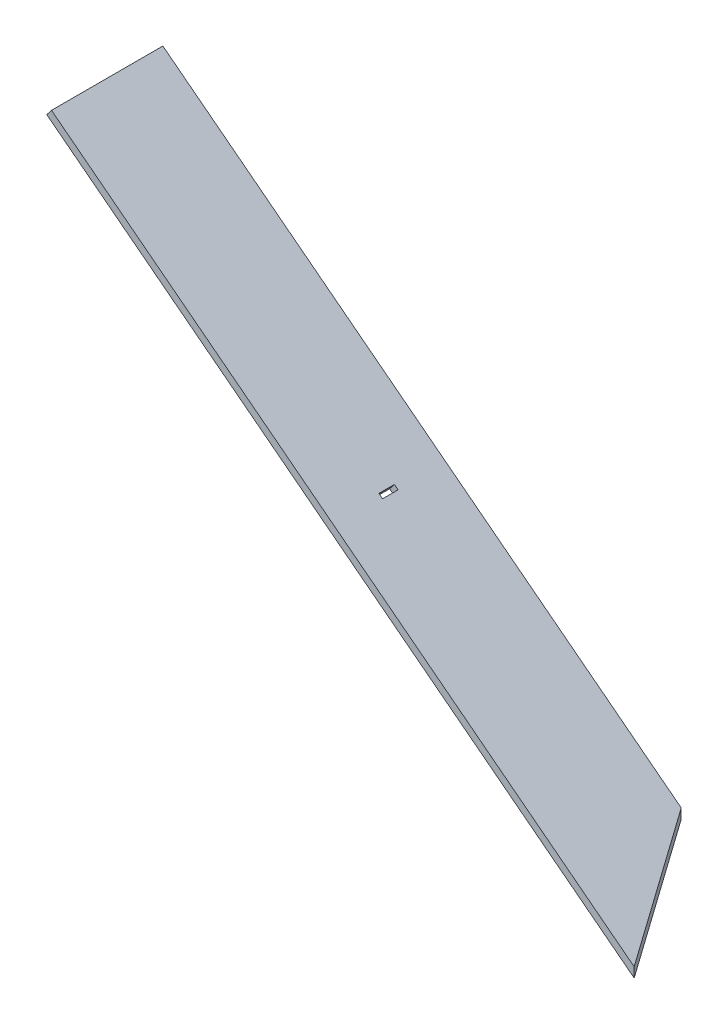
SolidWorks part; units mm, degrees
material "white foam"
ref_plane "Front Plane" through (0, 0, 0) normal (0, 0, 1) x (1, 0, 0)
ref_plane "Top Plane" through (0, 0, 0) normal (0, 1, 0) x (1, 0, 0)
ref_plane "Right Plane" through (0, 0, 0) normal (1, 0, 0) x (0, 0, -1)
sketch "Sketch1" plane through (0, 0, 0) normal (0, 0, 1) x (1, 0, 0)
  line L0 (0, 0) -> (380.0247, 293.7164)
  line L1 (0, 0) -> (-380.0247, 293.7164)
  line L2 (-380.0247, 0) -> (380.0247, 0) construction
  line L3 (0, 6.3193) -> (376.967, 297.6726)
  line L4 (0, 6.3193) -> (-376.967, 297.6726)
  line L5 (380.0247, 293.7164) -> (376.967, 297.6726)
  line L6 (-380.0247, 293.7164) -> (-376.967, 297.6726)
  point P7 (0, 0)
  dimension "D1" = 37.7
  dimension "D2" = 37.7
  dimension "D3" = 480.3
  dimension "D4" = 5
extrude "Boss-Extrude1" add sketch "Sketch1" against normal blind 240.2
sketch "Sketch2" plane through (0, 0, 0) normal (0, 1, 0) x (1, 0, 0)
  line L0 (-380.0247, 240.2) -> (-380.0247, 0) construction
  line L1 (380.0247, 240.2) -> (-380.0247, 240.2)
  line L2 (380.0247, 240.2) -> (380.0247, 168.14)
  line L3 (380.0247, 168.14) -> (-380.0247, 168.14)
  line L4 (-380.0247, 240.2) -> (-380.0247, 168.14)
  dimension "D1" = 72.06
extrude "Cut-Extrude3" cut sketch "Sketch2" along normal through all both and the other way through all flip side to cut contours L1 L4 L3 L2
sketch "Sketch3" plane through (0, 0, 0) normal (0, 1, 0) x (1, 0, 0)
  line L0 (0, 168.14) -> (41.6039, 240.2)
  line L1 (376.967, 240.2) -> (0, 240.2) construction
  line L2 (41.6039, 240.2) -> (-41.6039, 240.2)
  line L3 (-41.6039, 240.2) -> (0, 168.14)
  line L4 (0, 240.2) -> (0, 168.14) construction
  line L9 (380.0247, 168.14) -> (380.0247, 240.2)
  line L10 (0, 168.14) -> (380.0247, 168.14)
  line L11 (0, 240.2) -> (0, 168.14)
  line L12 (380.0247, 240.2) -> (0, 240.2)
  line L13 (380.0247, 168.14) -> (380.0247, 240.2)
  line L14 (0, 168.14) -> (380.0247, 168.14)
  line L16 (380.0247, 240.2) -> (0, 240.2)
  line L17 (0, 168.14) -> (0, 240.2)
  line L18 (-380.0247, 168.14) -> (0, 168.14)
  line L19 (-380.0247, 240.2) -> (-380.0247, 168.14)
  line L20 (0, 240.2) -> (-380.0247, 240.2)
  line L22 (-380.0247, 168.14) -> (0, 168.14)
  line L23 (-380.0247, 240.2) -> (-380.0247, 168.14)
  line L24 (0, 240.2) -> (-380.0247, 240.2)
  dimension "D1" = 60
  dimension "D2" = 30
  dimension "D3" = 0
  dimension "D4" = 0
extrude "Cut-Extrude4" cut sketch "Sketch3" along normal through all contours L13 L16 L0 L14 | L2 L3 L0
sketch "Sketch4" plane through (3.0576, 3.9561, 0) normal (0.6115, 0.7912, 0) x (0.7912, -0.6115, 0)
  line L0 (-242.0822, 168.14) -> (-242.0822, 240.2) construction
  line L1 (-480.3, 168.14) -> (-3.8644, 168.14) construction
  line L2 (-56.4461, 240.2) -> (-480.3, 240.2) construction
  line L4 (-251.7822, 199.17) -> (-248.7822, 199.17)
  line L5 (-251.7822, 199.17) -> (-251.7822, 209.17)
  line L6 (-251.7822, 209.17) -> (-248.7822, 209.17)
  line L7 (-248.7822, 199.17) -> (-248.7822, 209.17)
  line L8 (-251.7822, 199.17) -> (-248.7822, 209.17) construction
  line L9 (-251.7822, 209.17) -> (-248.7822, 199.17) construction
  point P7 (-250.2822, 204.17)
  point P12 (-242.0822, 204.17)
  dimension "D1" = 3
  dimension "D2" = 10
  dimension "D3" = 13.4
extrude "Cut-Extrude5" cut sketch "Sketch4" against normal through all both and the other way through all
sketch "Sketch5" plane through (3.0576, 3.9561, 0) normal (0.6115, 0.7912, 0) x (0.7912, -0.6115, 0)
  line L0 (-440.3, 204.17) -> (-295.3, 204.17) construction
  line L1 (-440.3, 225.2) -> (-295.3, 225.2)
  line L2 (-440.3, 183.14) -> (-295.3, 183.14)
  line L3 (-480.3, 168.14) -> (-3.8644, 168.14) construction
  line L4 (-56.4461, 240.2) -> (-480.3, 240.2) construction
  line L5 (-480.3, 240.2) -> (-480.3, 168.14) construction
  line L6 (-205.3, 204.17) -> (-75.3, 204.17) construction
  line L7 (-205.3, 225.2) -> (-75.3, 225.2)
  line L8 (-205.3, 183.14) -> (-75.3, 183.14)
  arc A0 (-440.3, 225.2) -> (-440.3, 183.14) centre (-440.3, 204.17) ccw
  arc A1 (-295.3, 183.14) -> (-295.3, 225.2) centre (-295.3, 204.17) ccw
  arc A2 (-205.3, 225.2) -> (-205.3, 183.14) centre (-205.3, 204.17) ccw
  arc A3 (-75.3, 183.14) -> (-75.3, 225.2) centre (-75.3, 204.17) ccw
  point P2 (-367.8, 204.17)
  point P13 (-140.3, 204.17)
  dimension "D1" = 15
  dimension "D2" = 15
  dimension "D3" = 145
  dimension "D4" = 40
  dimension "D5" = 15
  dimension "D6" = 90
  dimension "D7" = 130
extrude "Cut-Extrude6" [suppressed] cut sketch "Sketch5" against normal blind 10
equation "\"D3@Sketch4\"=12.4+1"
equation "\"D3@Sketch1\"=960.6/2"
equation "\"D1@Boss-Extrude1\"=240.2"
equation "\"D1@Sketch2\"=72.06"
